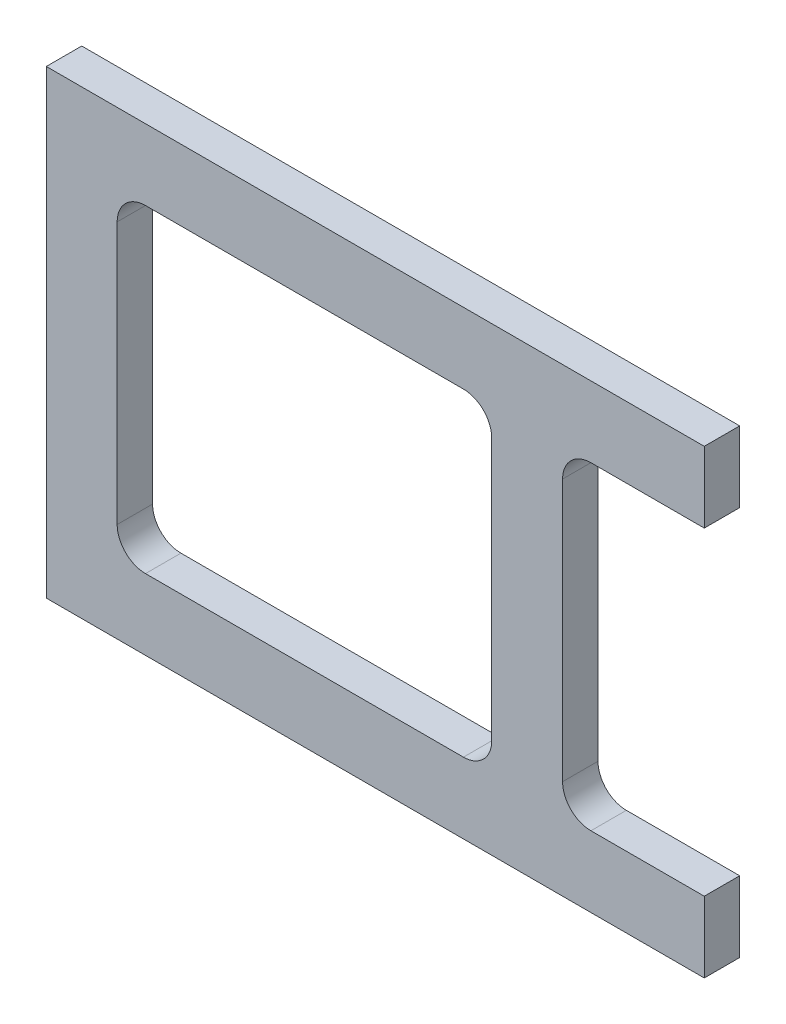
SolidWorks part; units mm, degrees
material "ABS PC"
ref_plane "Front Plane" through (0, 0, 0) normal (0, 0, 1) x (1, 0, 0)
ref_plane "Top Plane" through (0, 0, 0) normal (0, 1, 0) x (1, 0, 0)
ref_plane "Right Plane" through (0, 0, 0) normal (1, 0, 0) x (0, 0, -1)
sketch "Sketch1" plane through (0, 0, 0) normal (0, 0, 1) x (1, 0, 0)
  line L1 (-29.4894, -20.6375) -> (29.4894, -20.6375)
  line L2 (-29.4894, -20.6375) -> (-29.4894, 20.6375)
  line L3 (-29.4894, 20.6375) -> (29.4894, 20.6375)
  line L4 (29.4894, -20.6375) -> (29.4894, 20.6375)
  line L5 (-29.4894, -20.6375) -> (29.4894, 20.6375) construction
  line L6 (-29.4894, 20.6375) -> (29.4894, -20.6375) construction
  point P0 (0, 0)
  dimension "D1" = 58.9788
  dimension "D2" = 41.275
extrude "Boss-Extrude1" add sketch "Sketch1" along normal blind 3.175
sketch "Sketch2" plane through (0, 0, 3.175) normal (0, 0, 1) x (1, 0, 0)
  line L0 (29.4894, -20.6375) -> (29.4894, 20.6375) construction
  line L1 (29.4894, 14.2875) -> (16.7894, 14.2875)
  line L2 (29.4894, 14.2875) -> (29.4894, -14.2875)
  line L3 (29.4894, -14.2875) -> (16.7894, -14.2875)
  line L4 (16.7894, 14.2875) -> (16.7894, -14.2875)
  line L5 (29.4894, 20.6375) -> (29.4894, 14.2875) construction
  line L6 (29.4894, -14.2875) -> (29.4894, -20.6375) construction
  line L7 (-29.4894, 20.6375) -> (-29.4894, -20.6375) construction
  line L8 (10.4394, 14.2875) -> (-23.1394, 14.2875)
  line L9 (10.4394, 14.2875) -> (10.4394, -14.2875)
  line L10 (10.4394, -14.2875) -> (-23.1394, -14.2875)
  line L11 (-23.1394, 14.2875) -> (-23.1394, -14.2875)
  dimension "D1" = 28.575
  dimension "D2" = 12.7
  dimension "D3" = 6.35
  dimension "D4" = 6.35
extrude "Cut-Extrude1" cut sketch "Sketch2" against normal through all
fillet "Fillet1" radius 2.54 6 edges at (16.7894, -14.2875, 1.5875) (16.7894, 14.2875, 1.5875) (10.4394, 14.2875, 1.5875) (10.4394, -14.2875, 1.5875) (-23.1394, -14.2875, 1.5875) (-23.1394, 14.2875, 1.5875)
